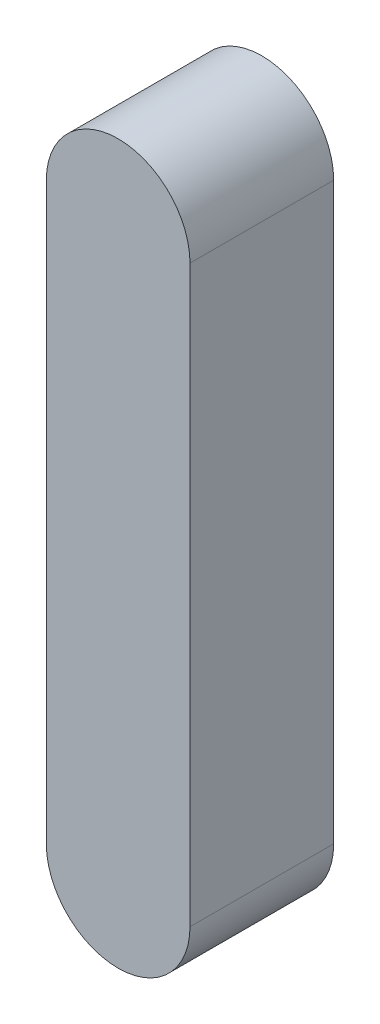
SolidWorks part; units mm, degrees
material "1.4511 (X3CrNb17)"
ref_plane "前视基准面" through (0, 0, 0) normal (0, 0, 1) x (1, 0, 0)
ref_plane "上视基准面" through (0, 0, 0) normal (0, 1, 0) x (1, 0, 0)
ref_plane "右视基准面" through (0, 0, 0) normal (1, 0, 0) x (0, 0, -1)
sketch "草图1" plane through (0, 0, 0) normal (0, 0, 1) x (1, 0, 0)
  line L0 (1, -4) -> (-1, 4) construction
  line L6 (-1, 4) -> (-1, -4)
  line L8 (1, 4) -> (1, -4)
  line L9 (1, 4) -> (-1, -4) construction
  arc A2 (1, 4) -> (-1, 4) centre (0, 4) ccw
  arc A3 (-1, -4) -> (1, -4) centre (0, -4) ccw
  point P0 (0, 0)
  point P5 (0, 0)
  dimension "D2" = 1
  dimension "D3" = 0
  dimension "D1" = 8
  dimension "D4" = 0
extrude "凸台-拉伸1" add sketch "草图1" along normal blind 2
